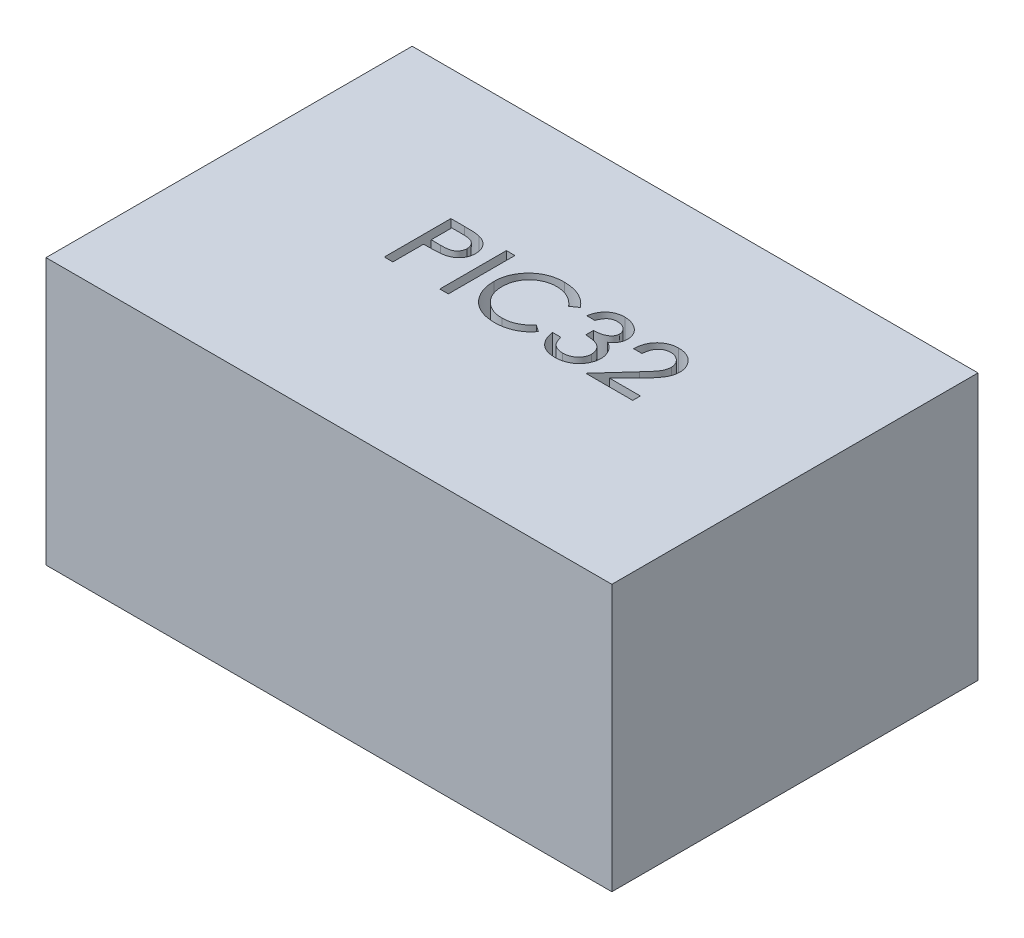
SolidWorks part; units mm, degrees
ref_plane "Front Plane" through (0, 0, 0) normal (0, 0, 1) x (1, 0, 0)
ref_plane "Top Plane" through (0, 0, 0) normal (0, 1, 0) x (1, 0, 0)
ref_plane "Right Plane" through (0, 0, 0) normal (1, 0, 0) x (0, 0, -1)
sketch "Sketch1" plane through (0, 0, 0) normal (0, 1, 0) x (1, 0, 0)
  line L1 (-26.9875, -17.4625) -> (26.9875, -17.4625)
  line L2 (-26.9875, -17.4625) -> (-26.9875, 17.4625)
  line L3 (-26.9875, 17.4625) -> (26.9875, 17.4625)
  line L4 (26.9875, -17.4625) -> (26.9875, 17.4625)
  line L5 (-26.9875, -17.4625) -> (26.9875, 17.4625) construction
  line L6 (-26.9875, 17.4625) -> (26.9875, -17.4625) construction
  point P0 (0, 0)
  dimension "D1" = 53.975
  dimension "D2" = 34.925
extrude "Boss-Extrude1" add sketch "Sketch1" along normal blind 25.4
sketch "Sketch2" plane through (0, 25.4, 0) normal (0, 1, 0) x (1, 0, 0)
  text T0 "<b>PIC32</b>" font "Century Gothic" height in points 24
extrude "Cut-Extrude1" cut sketch "Sketch2" against normal mid plane 25.4
